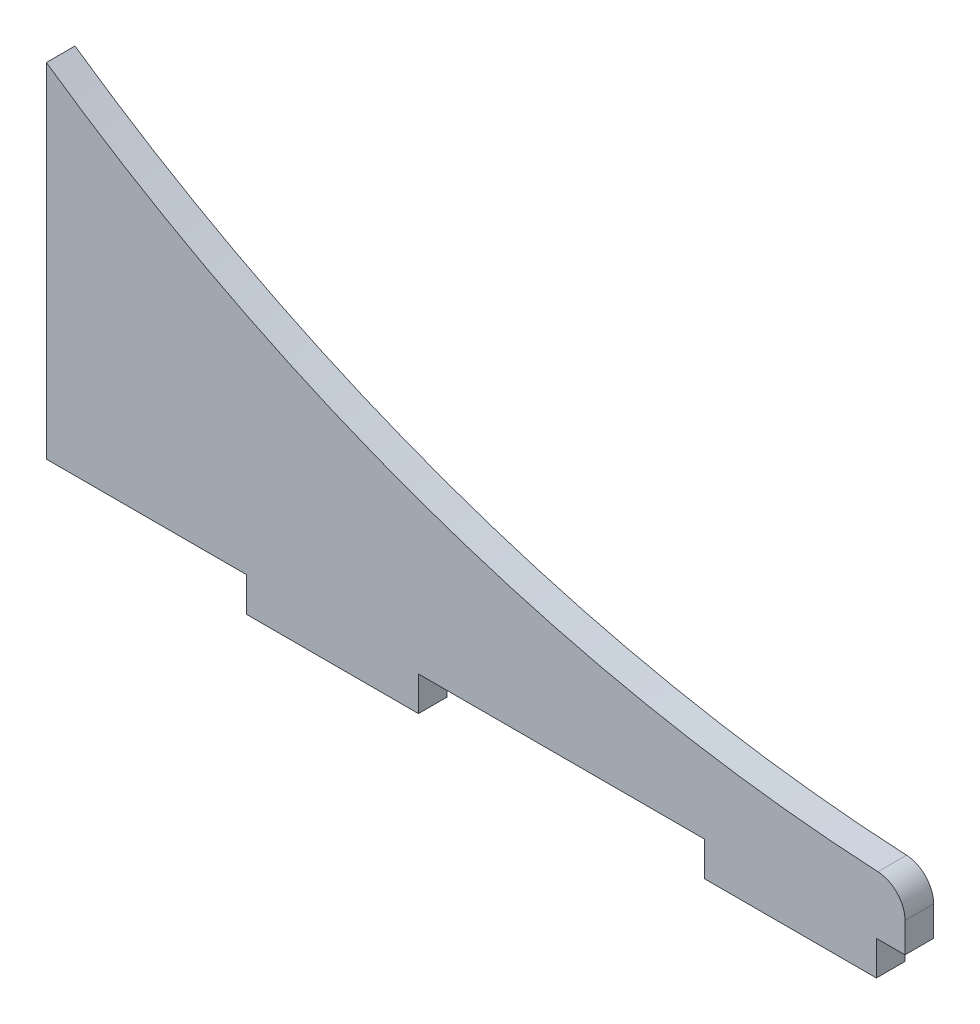
SolidWorks part; units mm, degrees
ref_plane "前视基准面" through (0, 0, 0) normal (0, 0, 1) x (1, 0, 0)
ref_plane "上视基准面" through (0, 0, 0) normal (0, 1, 0) x (1, 0, 0)
ref_plane "右视基准面" through (0, 0, 0) normal (1, 0, 0) x (0, 0, -1)
sketch "草图1" plane through (0, 0, 0) normal (0, 0, 1) x (1, 0, 0)
  line L4 (125, 0) -> (125, -6)
  line L5 (125, -6) -> (95, -6)
  line L6 (95, -6) -> (95, 0)
  line L7 (95, 0) -> (45, 0)
  line L8 (45, 0) -> (45, -6)
  line L9 (45, -6) -> (15, -6)
  line L10 (15, -6) -> (15, 0)
  line L11 (15, 0) -> (0, 0)
  line L14 (125, 0) -> (130, 0)
  line L15 (130, 10) -> (130, 0)
  line L16 (0, 0) -> (-20, 0)
  line L17 (-20, 0) -> (-20, 60)
  arc A1 (130, 10) -> (-20, 60) centre (139.9412, 289.8235) cw
  point P4 (0, 0)
extrude "凸台-拉伸1" add sketch "草图1" along normal blind 5
fillet "圆角1" radius 5 1 edges at (130, 10, 2.5)
